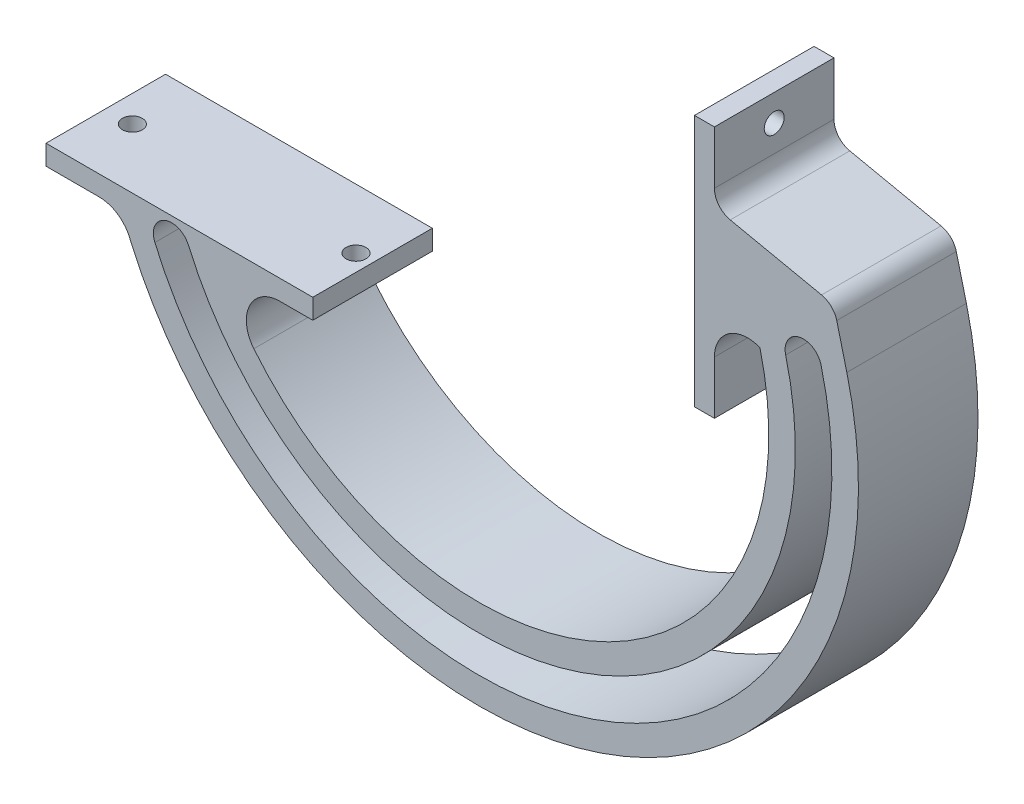
SolidWorks part; units mm, degrees
material "ABS"
ref_plane "Alzado" through (0, 0, 0) normal (0, 0, 1) x (1, 0, 0)
ref_plane "Planta" through (0, 0, 0) normal (0, 1, 0) x (1, 0, 0)
ref_plane "Vista lateral" through (0, 0, 0) normal (1, 0, 0) x (0, 0, -1)
curve "Curva8"
  spline degree 3 poles (-59.8184, 3.2889, 0) (-59.8153, 3.2817, 0) (-59.8027, 3.2526, 0) (-59.7743, 3.1874, 0) (-59.7269, 3.0788, 0) (-59.6601, 2.927, 0) (-59.5736, 2.7323, 0) (-59.4668, 2.4952, 0) (-59.3392, 2.2159, 0) (-59.1901, 1.8952, 0) (-59.0187, 1.5336, 0) (-58.8241, 1.1318, 0) (-58.6054, 0.6907, 0) (-58.3615, 0.2112, 0) (-58.0912, -0.3057, 0) (-57.7935, -0.8589, 0) (-57.4671, -1.4472, 0) (-57.1106, -2.0692, 0) (-56.7228, -2.7234, 0) (-56.3023, -3.4083, 0) (-55.8477, -4.1223, 0) (-55.3577, -4.8634, 0) (-54.8308, -5.6299, 0) (-54.2657, -6.4196, 0) (-53.661, -7.2305, 0) (-53.0155, -8.0601, 0) (-52.3278, -8.9062, 0) (-51.5968, -9.7661, 0) (-50.8214, -10.6374, 0) (-50.0005, -11.5171, 0) (-49.1333, -12.4026, 0) (-48.2188, -13.2908, 0) (-47.2564, -14.1788, 0) (-46.2456, -15.0633, 0) (-45.1859, -15.9412, 0) (-44.0772, -16.8093, 0) (-42.9193, -17.6643, 0) (-41.7124, -18.5027, 0) (-40.4568, -19.3213, 0) (-39.1529, -20.1165, 0) (-37.8015, -20.8851, 0) (-36.4035, -21.6236, 0) (-34.96, -22.3286, 0) (-33.4723, -22.997, 0) (-31.942, -23.6254, 0) (-30.3708, -24.2107, 0) (-28.7607, -24.7499, 0) (-27.1139, -25.2399, 0) (-25.4328, -25.678, 0) (-23.72, -26.0616, 0) (-21.9781, -26.3881, 0) (-20.2102, -26.6552, 0) (-18.4193, -26.8609, 0) (-16.6087, -27.0033, 0) (-14.7818, -27.0806, 0) (-12.942, -27.0914, 0) (-11.093, -27.0346, 0) (-9.2385, -26.9093, 0) (-7.3822, -26.7146, 0) (-5.5279, -26.4504, 0) (-3.6795, -26.1164, 0) (-1.8408, -25.7127, 0) (-0.0155, -25.2399, 0) (1.7925, -24.6986, 0) (3.5796, -24.0898, 0) (5.342, -23.4147, 0) (7.0763, -22.6748, 0) (8.779, -21.8719, 0) (10.4469, -21.0079, 0) (12.0768, -20.0852, 0) (13.6658, -19.106, 0) (15.2112, -18.0731, 0) (16.7102, -16.9893, 0) (18.1607, -15.8575, 0) (19.5605, -14.6809, 0) (20.9076, -13.4627, 0) (22.2004, -12.2065, 0) (23.4375, -10.9155, 0) (24.6177, -9.5935, 0) (25.7401, -8.244, 0) (26.8041, -6.8707, 0) (27.8092, -5.4772, 0) (28.7552, -4.0672, 0) (29.6422, -2.6444, 0) (30.4706, -1.2124, 0) (31.2408, 0.2252, 0) (31.9536, 1.6649, 0) (32.61, 3.1033, 0) (33.2111, 4.537, 0) (33.7582, 5.9629, 0) (34.253, 7.3778, 0) (34.697, 8.7787, 0) (35.0921, 10.1627, 0) (35.4402, 11.5271, 0) (35.7435, 12.8694, 0) (36.004, 14.1871, 0) (36.2242, 15.4779, 0) (36.4062, 16.7396, 0) (36.5525, 17.9704, 0) (36.6655, 19.1684, 0) (36.7477, 20.3318, 0) (36.8016, 21.4592, 0) (36.8297, 22.5491, 0) (36.8345, 23.6003, 0) (36.8184, 24.6116, 0) (36.7838, 25.5821, 0) (36.7332, 26.5108, 0) (36.6688, 27.397, 0) (36.5929, 28.24, 0) (36.5078, 29.0391, 0) (36.4155, 29.7941, 0) (36.3181, 30.5043, 0) (36.2175, 31.1695, 0) (36.1156, 31.7894, 0) (36.014, 32.3638, 0) (35.9145, 32.8925, 0) (35.8184, 33.3754, 0) (35.7272, 33.8124, 0) (35.6422, 34.2035, 0) (35.5645, 34.5485, 0) (35.4951, 34.8475, 0) (35.4348, 35.1006, 0) (35.3845, 35.3076, 0) (35.3448, 35.4685, 0) (35.316, 35.5835, 0) (35.2986, 35.6525, 0) (35.2909, 35.6832, 0) (35.2889, 35.6908, 0) knots 0 0 0 0 0.000158 0.000632 0.001421 0.002525 0.003943 0.005674 0.007718 0.010073 0.012737 0.015709 0.018987 0.022569 0.026452 0.030634 0.035113 0.039885 0.044949 0.050299 0.055934 0.061849 0.06804 0.074505 0.081238 0.088236 0.095494 0.103008 0.110772 0.118782 0.127033 0.135519 0.144236 0.153177 0.162337 0.171711 0.181292 0.191074 0.201051 0.211217 0.221566 0.23209 0.242784 0.25364 0.264652 0.275812 0.287114 0.29855 0.310114 0.321797 0.333593 0.345494 0.357493 0.369582 0.381753 0.393998 0.406311 0.418683 0.431106 0.443573 0.456075 0.468605 0.481155 0.493717 0.506283 0.518845 0.531395 0.543925 0.556427 0.568894 0.581317 0.593689 0.606002 0.618247 0.630418 0.642507 0.654506 0.666407 0.678203 0.689886 0.70145 0.712886 0.724188 0.735348 0.74636 0.757216 0.76791 0.778434 0.788783 0.798949 0.808926 0.818708 0.828289 0.837663 0.846823 0.855764 0.864481 0.872967 0.881218 0.889228 0.896992 0.904506 0.911764 0.918762 0.925495 0.93196 0.938151 0.944066 0.949701 0.955051 0.960115 0.964887 0.969366 0.973548 0.977431 0.981013 0.984291 0.987263 0.989927 0.992282 0.994326 0.996057 0.997475 0.998579 0.999368 0.999842 1 1 1 1
sketch "Croquis1" plane through (0, 0, 0) normal (0, 0, 1) x (1, 0, 0)
  arc A0 (-59.8184, 3.2889) -> (35.2889, 35.6908) centre (-13.5682, 23.3159) ccw construction
  arc A1 (-66.0126, 0.6067) -> (41.8323, 37.3482) centre (-13.5682, 23.3159) ccw
  arc A2 (-59.8184, 3.2889) -> (35.2889, 35.6908) centre (-13.5682, 23.3159) ccw construction
  arc A3 (-62.342, 2.1962) -> (37.9547, 36.3661) centre (-13.5682, 23.3159) ccw
  arc A4 (-57.2948, 4.3817) -> (32.6231, 35.0156) centre (-13.5682, 23.3159) ccw
  arc A5 (-57.2948, 4.3817) -> (-62.342, 2.1962) centre (-59.8184, 3.2889) ccw
  arc A6 (37.9547, 36.3661) -> (32.6231, 35.0156) centre (35.2889, 35.6908) ccw
  arc A7 (-53.6242, 5.9711) -> (28.7456, 34.0335) centre (-13.5682, 23.3159) ccw
  arc A8 (-53.6242, 5.9711) -> (-66.0126, 0.6067) centre (-59.8184, 3.2889) ccw
  arc A9 (41.8323, 37.3482) -> (28.7456, 34.0335) centre (35.2889, 35.6908) ccw
  spline S0 degree 3 poles (-1903.8195, -770.5434) (-64.1183, 18.3394) (-62.8963, 10.3732) (-59.6895, 2.992) (-59.3733, 2.2803) (-58.8219, 1.1105) (-57.9284, -0.642) (-56.7898, -2.6536) (-55.4952, -4.6831) (-54.2497, -6.458) (-53.0001, -8.0977) (-51.582, -9.8031) (-49.9862, -11.5535) (-48.2051, -13.3266) (-46.5818, -14.7848) (-45.1859, -15.9412) (-44.0772, -16.8093) (-42.9193, -17.6643) (-41.7124, -18.5027) (-40.4568, -19.3213) (-39.1529, -20.1165) (-37.8015, -20.8851) (-36.4035, -21.6236) (-34.96, -22.3286) (-33.4723, -22.997) (-31.942, -23.6254) (-30.3708, -24.2107) (-28.7607, -24.7499) (-27.1139, -25.2399) (-25.4328, -25.678) (-23.72, -26.0616) (-21.9781, -26.3881) (-20.2102, -26.6552) (-18.4193, -26.8609) (-16.6087, -27.0033) (-14.7818, -27.0806) (-12.942, -27.0914) (-11.093, -27.0346) (-9.2385, -26.9093) (-7.3822, -26.7146) (-5.5279, -26.4504) (-3.6795, -26.1164) (-1.8408, -25.7127) (-0.0155, -25.2399) (1.7925, -24.6986) (3.5796, -24.0898) (5.342, -23.4147) (7.0763, -22.6748) (8.779, -21.8719) (10.4469, -21.0079) (12.0768, -20.0852) (13.6658, -19.106) (15.2112, -18.0731) (16.7102, -16.9893) (18.1607, -15.8575) (19.5605, -14.6809) (20.9076, -13.4627) (22.2004, -12.2065) (23.4375, -10.9155) (24.6177, -9.5935) (25.7401, -8.244) (26.8041, -6.8707) (27.8092, -5.4772) (28.7552, -4.0672) (29.6422, -2.6444) (30.4706, -1.2124) (31.2408, 0.2252) (31.9536, 1.6649) (32.61, 3.1033) (33.2111, 4.537) (33.7582, 5.9629) (34.253, 7.3778) (34.697, 8.7787) (35.0921, 10.1627) (35.551, 11.961) (36.0151, 14.1507) (36.4171, 16.7025) (36.6763, 19.1304) (36.8124, 21.4204) (36.8453, 23.5606) (36.7946, 25.5415) (36.6636, 27.6087) (36.4447, 29.6805) (36.1032, 31.9521) (35.7568, 33.719) (35.4744, 34.9404) (35.362, 35.3996) (35.316, 35.5835) (33.4018, 43.1796) (29.5063, 50.2338) (1968.1321, 548.5845) knots -0.155026 -0.155026 -0.155026 -0.155026 0.000158 0.000632 0.005674 0.015709 0.026452 0.044949 0.061849 0.074505 0.088236 0.103008 0.118782 0.135519 0.153177 0.162337 0.171711 0.181292 0.191074 0.201051 0.211217 0.221566 0.23209 0.242784 0.25364 0.264652 0.275812 0.287114 0.29855 0.310114 0.321797 0.333593 0.345494 0.357493 0.369582 0.381753 0.393998 0.406311 0.418683 0.431106 0.443573 0.456075 0.468605 0.481155 0.493717 0.506283 0.518845 0.531395 0.543925 0.556427 0.568894 0.581317 0.593689 0.606002 0.618247 0.630418 0.642507 0.654506 0.666407 0.678203 0.689886 0.70145 0.712886 0.724188 0.735348 0.74636 0.757216 0.76791 0.778434 0.788783 0.798949 0.808926 0.818708 0.828289 0.837663 0.855764 0.872967 0.889228 0.904506 0.918762 0.93196 0.944066 0.960115 0.973548 0.989927 0.996057 0.998579 0.999368 0.999842 1.155003 1.155003 1.155003 1.155003 only from (-59.8184, 3.2889) to (35.2889, 35.6908) construction
  spline S1 degree 3 poles (-59.8184, 3.2889) (-59.8153, 3.2817) (-59.8027, 3.2526) (-59.6895, 2.992) (-59.3733, 2.2803) (-58.8219, 1.1105) (-57.9284, -0.642) (-56.7898, -2.6536) (-55.4952, -4.6831) (-54.2497, -6.458) (-53.0001, -8.0977) (-51.582, -9.8031) (-49.9862, -11.5535) (-48.2051, -13.3266) (-46.5818, -14.7848) (-45.1859, -15.9412) (-44.0772, -16.8093) (-42.9193, -17.6643) (-41.7124, -18.5027) (-40.4568, -19.3213) (-39.1529, -20.1165) (-37.8015, -20.8851) (-36.4035, -21.6236) (-34.96, -22.3286) (-33.4723, -22.997) (-31.942, -23.6254) (-30.3708, -24.2107) (-28.7607, -24.7499) (-27.1139, -25.2399) (-25.4328, -25.678) (-23.72, -26.0616) (-21.9781, -26.3881) (-20.2102, -26.6552) (-18.4193, -26.8609) (-16.6087, -27.0033) (-14.7818, -27.0806) (-12.942, -27.0914) (-11.093, -27.0346) (-9.2385, -26.9093) (-7.3822, -26.7146) (-5.5279, -26.4504) (-3.6795, -26.1164) (-1.8408, -25.7127) (-0.0155, -25.2399) (1.7925, -24.6986) (3.5796, -24.0898) (5.342, -23.4147) (7.0763, -22.6748) (8.779, -21.8719) (10.4469, -21.0079) (12.0768, -20.0852) (13.6658, -19.106) (15.2112, -18.0731) (16.7102, -16.9893) (18.1607, -15.8575) (19.5605, -14.6809) (20.9076, -13.4627) (22.2004, -12.2065) (23.4375, -10.9155) (24.6177, -9.5935) (25.7401, -8.244) (26.8041, -6.8707) (27.8092, -5.4772) (28.7552, -4.0672) (29.6422, -2.6444) (30.4706, -1.2124) (31.2408, 0.2252) (31.9536, 1.6649) (32.61, 3.1033) (33.2111, 4.537) (33.7582, 5.9629) (34.253, 7.3778) (34.697, 8.7787) (35.0921, 10.1627) (35.551, 11.961) (36.0151, 14.1507) (36.4171, 16.7025) (36.6763, 19.1304) (36.8124, 21.4204) (36.8453, 23.5606) (36.7946, 25.5415) (36.6636, 27.6087) (36.4447, 29.6805) (36.1032, 31.9521) (35.7568, 33.719) (35.4744, 34.9404) (35.362, 35.3996) (35.316, 35.5835) (35.2986, 35.6525) (35.2909, 35.6832) (35.2889, 35.6908) knots 0 0 0 0 0.000158 0.000632 0.005674 0.015709 0.026452 0.044949 0.061849 0.074505 0.088236 0.103008 0.118782 0.135519 0.153177 0.162337 0.171711 0.181292 0.191074 0.201051 0.211217 0.221566 0.23209 0.242784 0.25364 0.264652 0.275812 0.287114 0.29855 0.310114 0.321797 0.333593 0.345494 0.357493 0.369582 0.381753 0.393998 0.406311 0.418683 0.431106 0.443573 0.456075 0.468605 0.481155 0.493717 0.506283 0.518845 0.531395 0.543925 0.556427 0.568894 0.581317 0.593689 0.606002 0.618247 0.630418 0.642507 0.654506 0.666407 0.678203 0.689886 0.70145 0.712886 0.724188 0.735348 0.74636 0.757216 0.76791 0.778434 0.788783 0.798949 0.808926 0.818708 0.828289 0.837663 0.855764 0.872967 0.889228 0.904506 0.918762 0.93196 0.944066 0.960115 0.973548 0.989927 0.996057 0.998579 0.999368 0.999842 1 1 1 1
  point P5 (2.6851, -24.3914)
  point P7 (2.6851, -24.3914)
  dimension "D1" = 2.75
  dimension "D2" = 6.75
extrude "Saliente-Extruir2" add sketch "Croquis1" along normal mid plane 18 contours A1 A9 A7 A8 A6 A3 A5 A4
sketch "Croquis7" plane through (0, 0, -9) normal (0, 0, -1) x (-1, 0, 0)
  line L0 (38.5671, 6.9461) -> (54.145, 6.9461)
  line L1 (89.9037, 6.9461) -> (0.0037, 6.9461) construction
  line L5 (38.5671, 6.9461) -> (38.5671, 3.9461)
  line L6 (38.5671, 3.9461) -> (43.5671, 3.9461)
  arc A0 (-28.7456, 34.0335) -> (53.6242, 5.9711) centre (13.5682, 23.3159) ccw construction
  arc A1 (66.0126, 0.6067) -> (53.6242, 5.9711) centre (59.8184, 3.2889) ccw construction
  arc A2 (-28.7456, 34.0335) -> (47.448, -4.2065) centre (13.5682, 23.3159) ccw
  arc A3 (54.145, 6.9461) -> (53.6242, 5.9711) centre (59.8184, 3.2889) ccw
  arc A4 (47.448, -4.2065) -> (43.5671, 3.9461) centre (43.5671, -1.0539) ccw
  arc A5 (-28.7456, 34.0335) -> (53.6242, 5.9711) centre (13.5682, 23.3159) ccw
  arc M12 (66.0126, 0.6067) -> (53.6242, 5.9711) centre (59.8184, 3.2889) ccw
  arc M13 (53.6242, 5.9711) -> (-28.7456, 34.0335) centre (13.5682, 23.3159) cw
  dimension "D3" = 5
  dimension "D1" = 3
  dimension "D5" = 5
extrude "Saliente-Extruir4" add sketch "Croquis7" against normal blind 18 contours A4 L0 L5 L6 M13 M12
sketch "Croquis8" plane through (0, 0, -9) normal (0, 0, -1) x (-1, 0, 0)
  line L1 (54.145, 6.9461) -> (62.1693, 6.9461)
  line L2 (54.145, 6.9461) -> (54.145, 9.2446)
  line L3 (54.145, 9.2446) -> (62.1693, 9.2446)
  line L4 (62.1693, 6.9461) -> (62.1693, 9.2446)
  dimension "D1" = 2.2984
  dimension "D2" = 8.0243
extrude "Cortar-Extruir3" cut sketch "Croquis8" against normal through all both and the other way through all
sketch "Croquis9" plane through (0, 0, -9) normal (0, 0, -1) x (-1, 0, 0)
  line L1 (38.5671, 6.9461) -> (62.1693, 6.9461) construction
  line L2 (78.7288, 6.9461) -> (78.7288, 3.9461)
  line L3 (78.7288, 3.9461) -> (70.7288, 3.9461)
  line L6 (65.4918, 6.9461) -> (78.7288, 6.9461)
  arc A2 (70.7288, 3.9461) -> (66.0126, 0.6067) centre (70.7288, -1.0539) ccw
  arc A4 (66.0126, 0.6067) -> (56.6415, 9.2446) centre (59.8184, 3.2889) ccw construction
  arc A5 (66.0126, 0.6067) -> (65.4918, 6.9461) centre (59.8184, 3.2889) ccw
  arc M7 (66.0126, 0.6067) -> (56.6415, 9.2446) centre (59.8184, 3.2889) ccw
  dimension "D2" = 5
  dimension "D1" = 3
  dimension "D3" = 8
extrude "Saliente-Extruir5" add sketch "Croquis9" against normal blind 18 contours A2 L3 L2 L6 M7
sketch "Croquis10" plane through (0, 0, 9) normal (0, 0, 1) x (1, 0, 0)
  line L0 (18.8963, 296.1383) -> (18.8963, 0.0383) construction
  line L1 (18.8963, 21.388) -> (18.8963, 56.388)
  line L2 (18.8963, 296.1383) -> (18.8963, 0.0383)
  line L3 (18.8963, 56.388) -> (21.8963, 56.388)
  line L4 (21.8963, 56.388) -> (21.8963, 48.388)
  line L5 (24.1582, 45.4802) -> (36.9496, 42.2334)
  line L6 (18.8963, 21.388) -> (21.8963, 21.388)
  line L7 (21.8963, 21.388) -> (21.8963, 29.388)
  arc A0 (28.7456, 34.0335) -> (21.8963, 29.388) centre (26.8963, 29.388) ccw
  arc A1 (41.8323, 37.3482) -> (28.7456, 34.0335) centre (35.2889, 35.6908) ccw construction
  arc A2 (41.8323, 37.3482) -> (28.7456, 34.0335) centre (35.2889, 35.6908) ccw
  arc A3 (-47.448, -4.2065) -> (28.7456, 34.0335) centre (-13.5682, 23.3159) ccw construction
  arc A4 (-47.448, -4.2065) -> (28.7456, 34.0335) centre (-13.5682, 23.3159) ccw
  arc A6 (21.8963, 48.388) -> (24.1582, 45.4802) centre (24.8963, 48.388) ccw
  arc A7 (-47.448, -4.2065) -> (28.7456, 34.0335) centre (-13.5682, 23.3159) ccw
  arc M16 (41.8323, 37.3482) -> (28.7456, 34.0335) centre (35.2889, 35.6908) ccw
  dimension "D1" = 3
  dimension "D2" = 3
  dimension "D3" = 3
  dimension "D4" = 5
  dimension "D6" = 8
  dimension "D7" = 8
  dimension "D8" = 35
extrude "Saliente-Extruir6" add sketch "Croquis10" against normal blind 18 contours A6 L4 L3 L1 L6 L7 A0 L5 M16
sketch "Croquis12" plane through (0, 0, -9) normal (0, 0, -1) x (-1, 0, 0)
  line L0 (-41.8323, 37.3482) -> (-40.3126, 43.3482)
  line L1 (-38.0248, 45.5467) -> (-24.2759, 48.4529)
  line L2 (-21.8963, 51.388) -> (-21.8963, 59.388)
  line L3 (-21.8963, 59.388) -> (-18.8963, 59.388)
  line L4 (-18.8963, 0.0383) -> (-18.8963, 296.1383) construction
  line L7 (-18.8963, 21.388) -> (-21.8963, 21.388) construction
  line L8 (-21.8963, 21.388) -> (-21.8963, 29.388) construction
  line L9 (-18.8963, 21.388) -> (-18.8963, 56.388) construction
  line L10 (-18.8963, 21.388) -> (-21.8963, 21.388)
  line L11 (-21.8963, 21.388) -> (-21.8963, 29.388)
  line L12 (-18.8963, 59.388) -> (-18.8963, 21.388)
  line L13 (-41.8323, 37.3482) -> (-37.9547, 36.3661)
  line L14 (-32.6231, 35.0156) -> (-28.7456, 34.0335)
  arc A0 (-21.8963, 51.388) -> (-24.2759, 48.4529) centre (-24.8963, 51.388) cw
  arc A1 (-38.0248, 45.5467) -> (-40.3126, 43.3482) centre (-37.4044, 42.6116) ccw
  arc A2 (-21.8963, 29.388) -> (-28.7456, 34.0335) centre (-26.8963, 29.388) ccw construction
  arc A3 (-32.6231, 35.0156) -> (-37.9547, 36.3661) centre (-35.2889, 35.6908) ccw construction
  arc A4 (-21.8963, 29.388) -> (-28.7456, 34.0335) centre (-26.8963, 29.388) ccw
  arc A5 (-32.6231, 35.0156) -> (-37.9547, 36.3661) centre (-35.2889, 35.6908) ccw
  dimension "D2" = 3
  dimension "D3" = 3
  dimension "D1" = 3
  dimension "D4" = 8
  dimension "D5" = 38
  dimension "D6" = 35
  dimension "D7" = 6
extrude "Saliente-Extruir7" add sketch "Croquis12" against normal blind 18
sketch "Croquis13" plane through (21.8963, 0, 0) normal (1, 0, 0) x (0, 0, -1)
  line L4 (-9, 51.388) -> (9, 51.388)
  line L5 (9, 51.388) -> (9, 59.388)
  line L6 (9, 59.388) -> (-9, 59.388)
  line L7 (-9, 59.388) -> (-9, 51.388)
  line L8 (-9, 51.388) -> (9, 51.388)
  line L9 (9, 51.388) -> (9, 59.388)
  line L10 (9, 59.388) -> (-9, 59.388)
  line L11 (-9, 59.388) -> (-9, 51.388)
  circle A0 centre (0, 55.388) radius 1.5
  point P6 (-9, 55.388)
  point P7 (0, 51.388)
  dimension "D2" = 3
  dimension "D1" = 0
extrude "Cortar-Extruir5" cut sketch "Croquis13" against normal through all both and the other way through all contours A0
sketch "Croquis14" plane through (21.8963, 0, 0) normal (1, 0, 0) x (0, 0, -1)
  line L0 (9, 21.388) -> (-9, 21.388) construction
  line L1 (-9, 21.388) -> (-9, 29.388) construction
  line L2 (-9, 21.388) -> (-9, 29.388)
  circle A0 centre (0, 25.388) radius 1.5
  point P4 (0, 21.388)
  point P8 (-9, 25.388)
  dimension "D1" = 3
extrude "Cortar-Extruir7" cut sketch "Croquis14" against normal mid plane 8 contours A0
sketch "Croquis15" plane through (0, 3.9461, 0) normal (0, -1, 0) x (1, 0, 0)
  line L1 (-78.7288, 9) -> (-78.7288, -9) construction
  line L2 (-78.7288, -9) -> (-70.7288, -9) construction
  line L3 (-78.7288, 9) -> (-78.7288, -9)
  line L5 (-78.7288, -9) -> (-70.7288, -9)
  circle A0 centre (-74.7288, 0) radius 1.5
  point P2 (-74.7288, -9)
  point P7 (-78.7288, 0)
  dimension "D1" = 3
extrude "Cortar-Extruir8" cut sketch "Croquis15" against normal through all contours A0
sketch "Croquis16" plane through (0, 3.9461, 0) normal (0, -1, 0) x (1, 0, 0)
  line L1 (-38.5671, 9) -> (-38.5671, -9) construction
  line L2 (-38.5671, -9) -> (-43.5671, -9) construction
  line L3 (-38.5671, 9) -> (-38.5671, -9)
  line L4 (-38.5671, -9) -> (-43.5671, -9)
  circle A0 centre (-41.0671, 0) radius 1.5
  point P6 (-41.0671, -9)
  point P7 (-38.5671, 0)
  dimension "D1" = 3
extrude "Cortar-Extruir9" cut sketch "Croquis16" against normal through all contours A0
sketch "Croquis17" plane through (0, 0, 9) normal (0, 0, 1) x (1, 0, 0)
  line L1 (-65.4918, 6.9461) -> (-50.4182, 6.9461)
  line L2 (-65.4918, 6.9461) -> (-65.4918, 15.0055)
  line L3 (-65.4918, 15.0055) -> (-50.4182, 15.0055)
  line L4 (-50.4182, 6.9461) -> (-50.4182, 15.0055)
  dimension "D1" = 15.0736
  dimension "D2" = 8.0594
extrude "Cortar-Extruir10" cut sketch "Croquis17" against normal through all both and the other way through all
